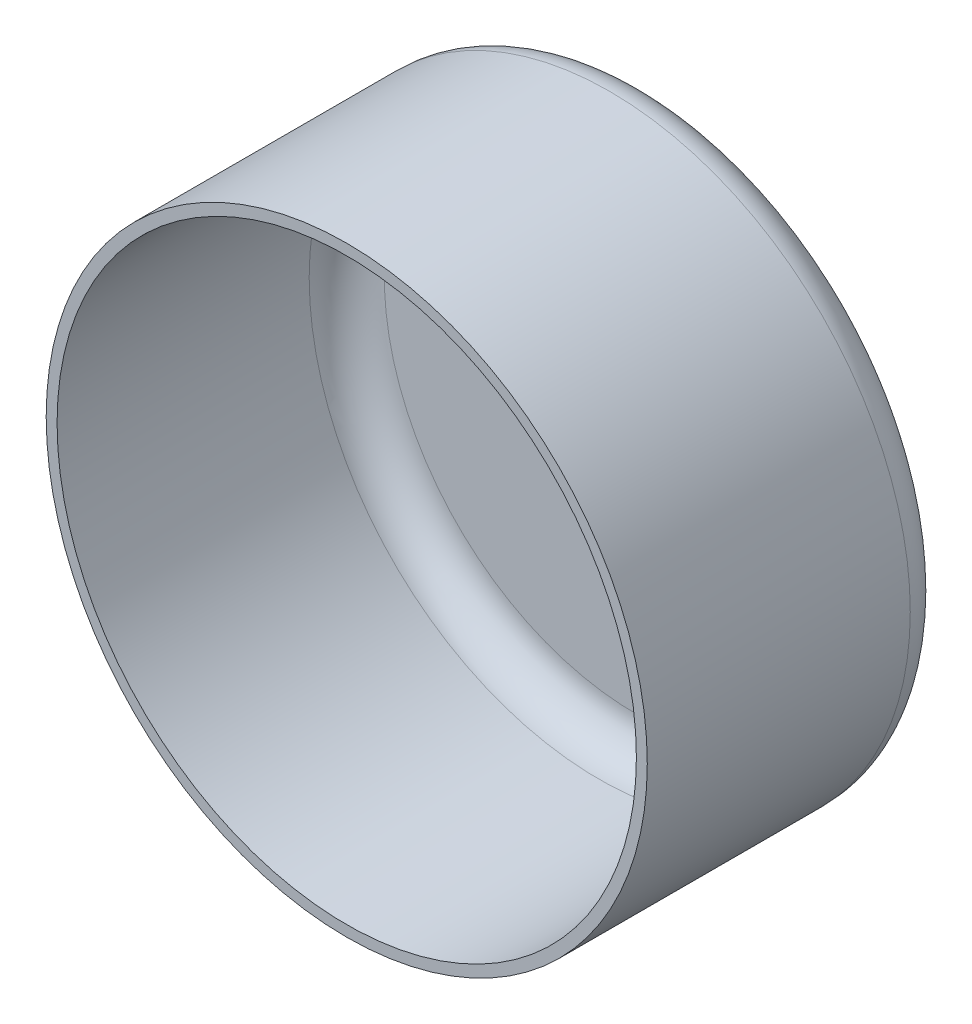
SolidWorks part; units mm, degrees
material "PET"
ref_plane "Ebene vorne" through (0, 0, 0) normal (0, 0, 1) x (1, 0, 0)
ref_plane "Ebene oben" through (0, 0, 0) normal (0, 1, 0) x (1, 0, 0)
ref_plane "Ebene rechts" through (0, 0, 0) normal (1, 0, 0) x (0, 0, -1)
sketch "Sketch1" plane through (0, 0, 0) normal (0, 0, 1) x (1, 0, 0)
  circle A0 centre (0, 0) radius 40
extrude "Boss-Extrude1" add sketch "Sketch1" along normal blind 40
shell "Shell1" thickness 1.45
fillet "Fillet1" radius 5 2 edges at (40, 0, 0) (38.55, 0, 1.45)
